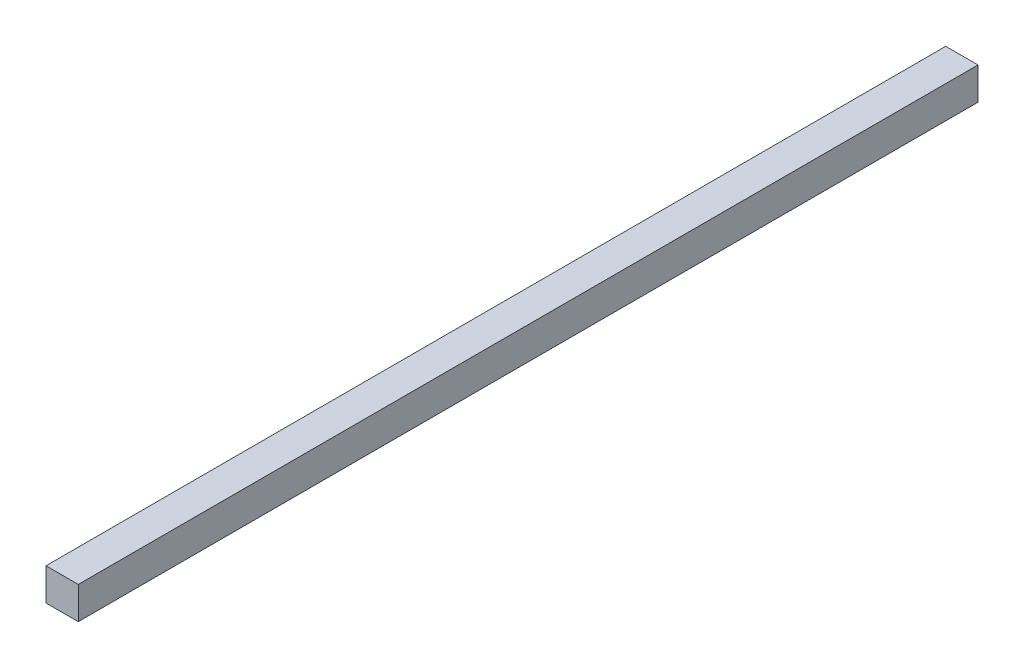
SolidWorks part; units mm, degrees
ref_plane "前视基准面" through (0, 0, 0) normal (0, 0, 1) x (1, 0, 0)
ref_plane "上视基准面" through (0, 0, 0) normal (0, 1, 0) x (1, 0, 0)
ref_plane "右视基准面" through (0, 0, 0) normal (1, 0, 0) x (0, 0, -1)
other "Configuration Table"
sketch "草图1" plane through (0, 0, 0) normal (0, 0, 1) x (1, 0, 0)
  line L1 (-21.7667, 18.3569) -> (-7.4177, 18.3569)
  line L2 (-21.7667, 18.3569) -> (-21.7667, 4.0079)
  line L3 (-21.7667, 4.0079) -> (-7.4177, 4.0079)
  line L4 (-7.4177, 18.3569) -> (-7.4177, 4.0079)
  line L5 (-21.7667, 18.3569) -> (-7.4177, 4.0079) construction
  line L6 (-21.7667, 4.0079) -> (-7.4177, 18.3569) construction
  point P0 (-14.5922, 11.1824)
extrude "凸台-拉伸1" add sketch "草图1" along normal blind 400
